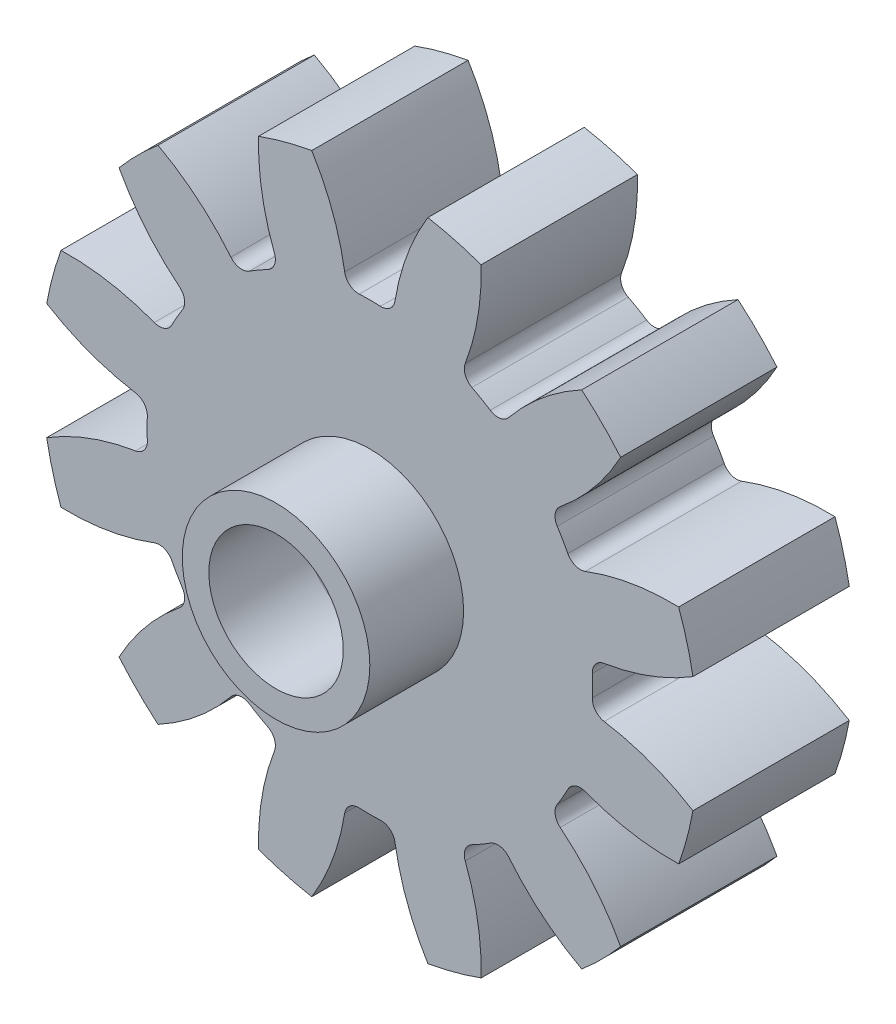
SolidWorks part; units mm, degrees
ref_plane "Front Plane" through (0, 0, 0) normal (0, 0, 1) x (1, 0, 0)
ref_plane "Top Plane" through (0, 0, 0) normal (0, 1, 0) x (1, 0, 0)
ref_plane "Right Plane" through (0, 0, 0) normal (1, 0, 0) x (0, 0, -1)
sketch "Sketch1" plane through (0, 0, 0) normal (0, 0, 1) x (1, 0, 0)
  circle A0 centre (0, 0) radius 9
  circle A1 centre (0, 0) radius 10.5
  circle A2 centre (0, 0) radius 7.125
  dimension "D1" = 18
  dimension "D2" = 21
  dimension "D4" = 3.375
extrude "Boss-Extrude1" add sketch "Sketch1" along normal mid plane 5 contours A1
sketch "Sketch2" plane through (0, 0, 0) normal (0, 0, 1) x (1, 0, 0)
  line L0 (0, 0) -> (0, 10.5) construction
  line L1 (-1.1747, 8.923) -> (1.1747, 8.923) construction
  line L2 (-0.7498, 7.0854) -> (0, 0) construction
  line L3 (-2.0459, 11.3165) -> (0, 5.6954) construction
  line L4 (0, 0) -> (2.7176, 10.1422) construction
  line L5 (1.1747, 8.923) -> (3.4442, 8.3149) construction
  circle A0 centre (0, 0) radius 10.5 construction
  arc A1 (-2.4962, 11.2258) -> (-0.7498, 7.0854) centre (-8.4673, 6.2687) cw
  arc A2 (2.4962, 11.2258) -> (0.7498, 7.0854) centre (8.4673, 6.2687) ccw
  circle A3 centre (0, 0) radius 7.125 construction
  circle A4 centre (0, 0) radius 10.5 construction
  arc A5 (0.7498, 7.0854) -> (-0.7498, 7.0854) centre (0, 0) ccw
  circle A6 centre (0, 0) radius 11.5
  arc A7 (2.4962, 11.2258) -> (-2.4962, 11.2258) centre (0, 0) ccw
  circle A8 centre (0, 0) radius 9 construction
  dimension "D2" = 20
  dimension "D3" = 15
  dimension "D1" = 1
extrude "Cut-Extrude1" cut sketch "Sketch2" against normal through all both and the other way through all
fillet "Fillet1" radius 0.45 2 edges at (0.7498, 7.0854, 0) (-0.7498, 7.0854, 0)
pattern_circular "CirPattern1" count 12 over 360 about axis through (0, 0, 0) along (0, 0, 1) of "Fillet1", "Cut-Extrude1"
sketch "Sketch3" plane through (0, 0, 2.5) normal (0, 0, 1) x (1, 0, 0)
  circle A0 centre (0, 0) radius 3
  circle A1 centre (0, 0) radius 2.15
  dimension "D1" = 6
  dimension "D2" = 4.3
extrude "Boss-Extrude2" add sketch "Sketch3" along normal blind 3
sketch "Sketch7" plane through (0, 0, 2.5) normal (0, 0, 1) x (1, 0, 0)
  circle A0 centre (0.8364, -2.2154) radius 0.218
  circle A1 centre (-0.3317, 2.0913) radius 0.0326
sketch "Sketch8" plane through (0, 0, 2.5) normal (0, 0, 1) x (1, 0, 0)
  circle A0 centre (0.0061, 0.0096) radius 2.1613
extrude "Cut-Extrude5" cut sketch "Sketch8" against normal blind 1
equation "\"module\"= 1.5mm"
equation "\"No. of teeth\" = 12"
equation "\"D1@Sketch1\"=\"module\"*\"No. of teeth\""
equation "\"D2@Sketch1\"=(\"No. of teeth\" + 2)* \"module\""
equation "\"D4@Sketch1\" = \"module\" * IIF ( \"module\" = > 1.25 , 2.25 , 2.4 )"
equation "\"D3@Sketch2\"=180 /  \"No. of teeth\""
equation "\"D1@Fillet1\"= .3 * \"module\""
